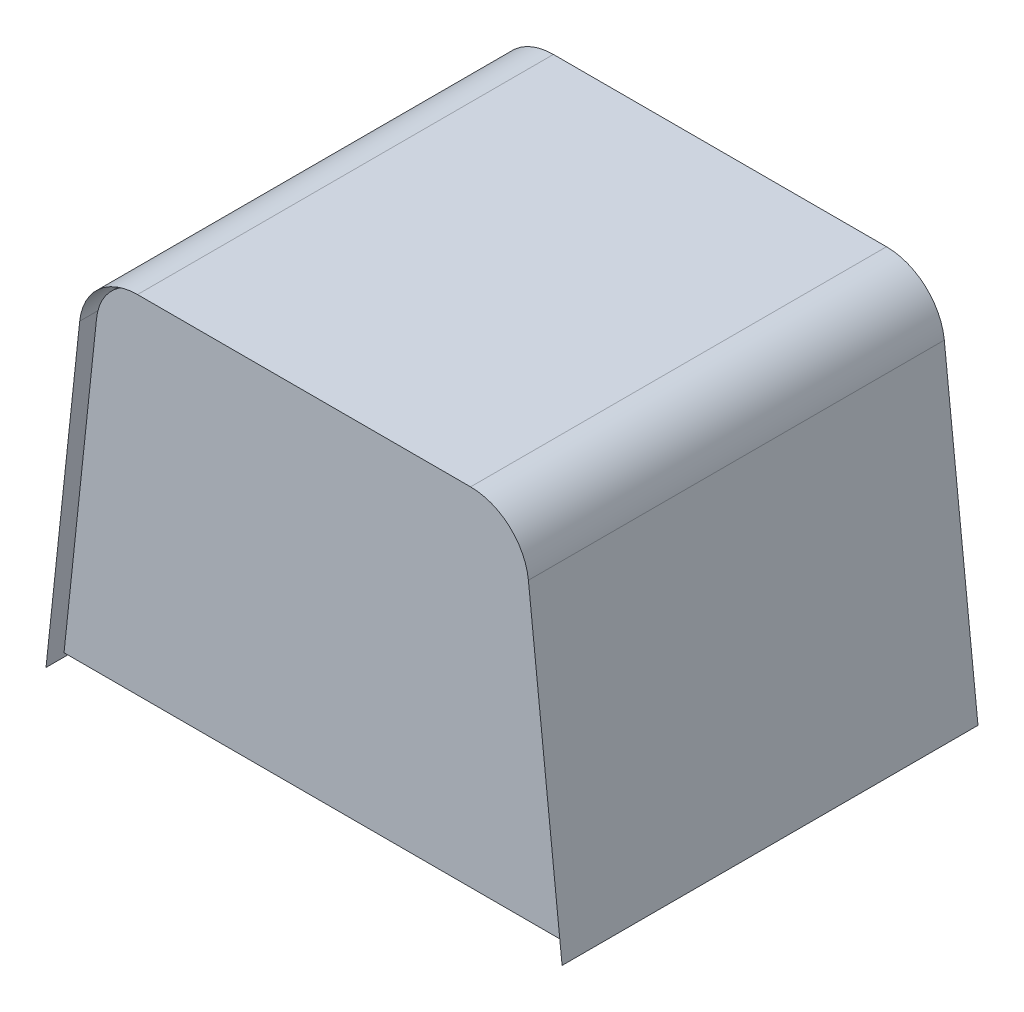
SolidWorks part; units mm, degrees
ref_plane "Front Plane" through (0, 0, 0) normal (0, 0, 1) x (1, 0, 0)
ref_plane "Top Plane" through (0, 0, 0) normal (0, 1, 0) x (1, 0, 0)
ref_plane "Right Plane" through (0, 0, 0) normal (1, 0, 0) x (0, 0, -1)
sketch "Sketch1" plane through (0, 0, 0) normal (0, 1, 0) x (1, 0, 0)
  line L0 (225.65, -262.25) -> (344.3325, -262.25)
  line L1 (-225.65, 262.25) -> (225.65, 262.25)
  line L2 (-225.65, 262.25) -> (-225.65, -262.25)
  line L3 (-225.65, -262.25) -> (225.65, -262.25)
  line L4 (225.65, 262.25) -> (225.65, -262.25) construction
  line L5 (-225.65, 262.25) -> (225.65, -262.25) construction
  line L6 (-225.65, -262.25) -> (225.65, 262.25) construction
  line L7 (344.3325, -262.25) -> (344.3325, 262.25)
  line L8 (344.3325, 262.25) -> (225.65, 262.25)
  point P0 (0, 0)
  dimension "D1" = 451.3
  dimension "D2" = 524.5
extrude "Boss-Extrude3" add sketch "Sketch1" along normal blind 370 contours L3 L0 L7 L8 L1 L2
sketch "Sketch3" plane through (0, 370, 0) normal (0, 1, 0) x (1, 0, 0)
  line L4 (-225.65, 262.25) -> (-225.65, -262.25)
  line L5 (-225.65, -262.25) -> (344.3325, -262.25)
  line L6 (344.3325, -262.25) -> (344.3325, 262.25)
  line L7 (344.3325, 262.25) -> (-225.65, 262.25)
  line L8 (-225.65, 262.25) -> (-225.65, -262.25)
  line L9 (-225.65, -262.25) -> (344.3325, -262.25)
  line L10 (344.3325, -262.25) -> (344.3325, 262.25)
  line L11 (344.3325, 262.25) -> (-225.65, 262.25)
  dimension "D1" = 0
extrude "Boss-Extrude4" add sketch "Sketch3" along normal blind 100
sketch "Sketch6" plane through (0, 0, 262.25) normal (0, 0, 1) x (1, 0, 0)
  line L0 (-225.65, 0) -> (-275.65, 0)
  line L1 (-275.65, 0) -> (-225.65, 470)
  line L2 (344.3325, 470) -> (394.3325, 0)
  line L3 (394.3325, 0) -> (344.3325, 0)
  line L4 (-225.65, 470) -> (344.3325, 470)
  line L5 (344.3325, 0) -> (-225.65, 0)
  dimension "D1" = 50
extrude "Boss-Extrude5" add sketch "Sketch6" against normal through all
fillet "Fillet3" radius 70 2 edges at (344.3325, 470, 0) (-225.65, 470, 0)
surface "Surface-Offset1" parameters "D1"=7.5
surface "Surface-Extend3" parameters "D1"=15, "D2"=15, "D3"=15, "D4"=15, "D5"=15
